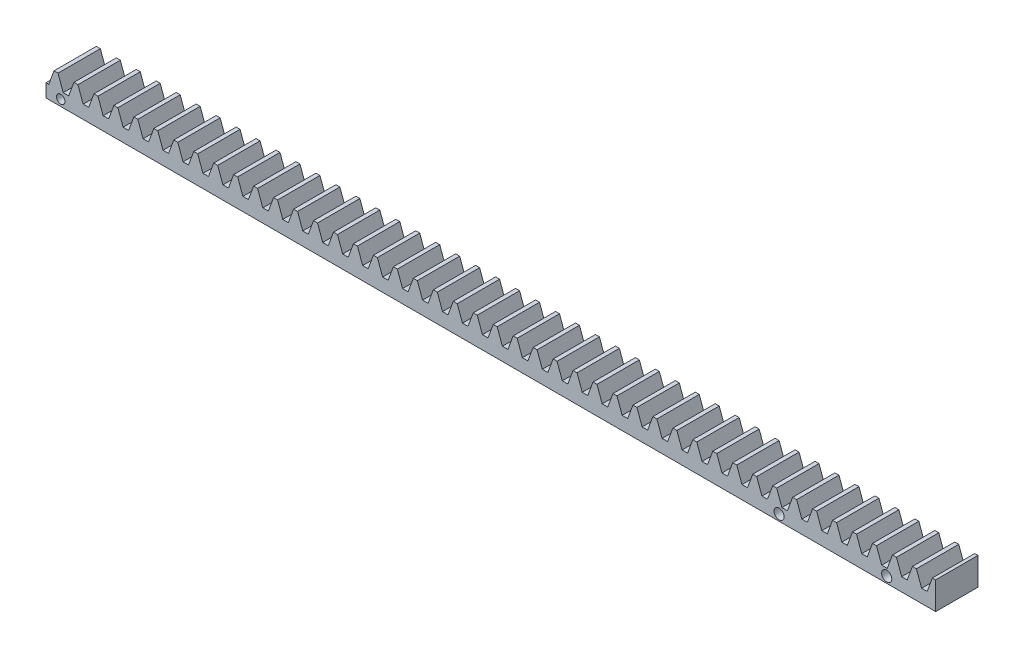
SolidWorks part; units mm, degrees
extrude "Blank" add sketch "BlankSke" against normal blind 10
sketch "BlankSke" plane through (0, 0, 0) normal (0, 0, 1) x (1, 0, 0)
  line L1 (0, 0) -> (210, 0)
  line L2 (0, 0) -> (0, 6.5)
  line L3 (0, 6.5) -> (210, 6.5)
  line L4 (210, 0) -> (210, 6.5)
  dimension "Length" = 210
  dimension "Blank_height" = 6.5
ref_plane "Plane1" through (0, 0, 0) normal (0, 0, 1) x (1, 0, 0)
ref_plane "Plane2" through (0, 0, 0) normal (0, 1, 0) x (1, 0, 0)
ref_plane "Plane3" through (0, 0, 0) normal (1, 0, 0) x (0, 0, -1)
sketch "HoldingSke" plane through (0, 0, 0) normal (0, 1, 0) x (1, 0, 0)
  line L0 (0, 0) -> (0.0928, 0.6602)
  line L1 (-15, 0) -> (100, 0) construction
  line L2 (0, 0) -> (-2.1039, 2.3779)
  line L3 (0, 0) -> (-11.863, 4.5341)
  line L4 (0, 0) -> (5.9991, 6.2122)
  line L5 (0, 0) -> (-23.7986, -8.8762)
  line L6 (0, 0) -> (-10.5278, -7.1032)
  line L9 (-71.009, 38.7566) -> (126.3265, 110.5808)
  line L10 (-76.2, 3.8779) -> (-71.2, 3.8779)
  line L11 (0, 0) -> (-10, 0)
  line L12 (-76.2, 101.6) -> (-76.147, 101.6)
  line L13 (24.9733, 27.94) -> (52.9518, 28.4284)
  line L14 (24.9733, 27.94) -> (24.9743, 27.94)
  line L15 (24.9733, 27.94) -> (100.4006, 29.5858)
  circle A0 centre (0, 0) radius 19.05
  circle A1 centre (0, 0) radius 2.5
  circle A2 centre (0, 0) radius 12.7
  dimension "MPH" = 5
  dimension "Diameter" = 38.1
  dimension "Num_teeth" = 46
  dimension "Pitch" = 0.6667
  dimension "Show_teeth" = 998
  dimension "Thickness" = 12.7
  dimension "Ap" = 20
  dimension "Pitch_height" = 5
  dimension "Width" = 10
  dimension "Backlash" = 0.053
  dimension "Addendum_fac" = 1
  dimension "Dedendum_fac" = 1.25
  dimension "Clearance_fac" = 0.25
  dimension "Dedendum_add" = 0.001
  dimension "Length" = 210
  dimension "Module" = 1.5
sketch "TooCutSkeIll" plane through (0, 0, 0) normal (0, 0, 1) x (1, 0, 0)
  line L0 (-1.8687, 6.4605) -> (-0.7447, 3.3724)
  line L1 (-0.3914, 3.125) -> (0.3914, 3.125)
  line L2 (0.7447, 3.3724) -> (1.8687, 6.4605)
  line L3 (210, 6.5) -> (0, 6.5) construction
  line L4 (0, 0) -> (0, 64.897) construction
  line L5 (-13.208, 5) -> (12.954, 5) construction
  line L6 (0, 0) -> (210, 0) construction
  line L7 (1.3371, 5) -> (1.3371, 48.7463) construction
  line L8 (-1.3371, 5) -> (-1.3371, 48.7463) construction
  line L9 (1.9251, 6.5) -> (1.9251, 6.5254)
  line L10 (-1.9251, 6.5) -> (-1.9251, 6.5254)
  line L11 (-1.9251, 6.5254) -> (1.9251, 6.5254)
  arc A0 (0.3914, 3.125) -> (0.7447, 3.3724) centre (0.3914, 3.501) ccw
  arc A1 (-0.7447, 3.3724) -> (-0.3914, 3.125) centre (-0.3914, 3.501) ccw
  arc A2 (1.9251, 6.5) -> (1.8687, 6.4605) centre (1.9251, 6.44) ccw
  arc A3 (-1.8687, 6.4605) -> (-1.9251, 6.5) centre (-1.9251, 6.44) ccw
  dimension "Pitch_height" = 5
  dimension "Addendum_plus" = 1.5254
  dimension "Pressure_angle" = 20
  dimension "Gap_width" = 2.6742
  dimension "Dedendum" = 1.875
extrude "ToothCutIll" [suppressed] cut sketch "TooCutSkeIll" against normal through all
sketch "TooCutSkeSim" plane through (0, 0, 0) normal (0, 0, 1) x (1, 0, 0)
  line L0 (0.6547, 3.125) -> (-0.6547, 3.125)
  line L1 (1.8923, 6.5254) -> (0.6547, 3.125)
  line L2 (0, 17.4625) -> (0, 53.467) construction
  line L3 (1.8923, 6.5254) -> (-1.8923, 6.5254)
  line L6 (-1.8923, 6.5254) -> (-0.6547, 3.125)
  line L9 (-1.3371, 5) -> (1.3371, 5) construction
  line L10 (0, 0) -> (210, 0) construction
  line L11 (1.3371, 5) -> (1.3371, 53.467) construction
  line L12 (-1.3371, 5) -> (-1.3371, 53.467) construction
  dimension "Pitch_height" = 5
  dimension "Addendum_plus" = 1.5254
  dimension "Pressure_angle" = 20
  dimension "Gap_width" = 2.6742
  dimension "Dedendum" = 1.875
extrude "ToothCutSim" cut sketch "TooCutSkeSim" against normal through all
pattern_linear "TeethCuts" count 45 spacing 4.7124 along (1, 0, 0) of "ToothCutIll", "ToothCutSim"
sketch "Sketch1" plane through (0, 0, -10) normal (0, 0, -1) x (-1, 0, 0)
  line L0 (0, 0) -> (-210, 0) construction
  line L1 (-199.6484, 1.5) -> (-3.4664, 1.5) construction
  circle A0 centre (-3.4664, 1.5) radius 1
  circle A2 centre (-198.4484, 1.5) radius 1.2
  circle A3 centre (-173.0484, 1.5) radius 1.2
  dimension "D2" = 1.5
  dimension "D3" = 25.4
extrude "Cut-Extrude1" cut sketch "Sketch1" against normal blind 10
equation "' \"Module@HoldingSke\" = 6.35"
equation "' \"Num_teeth@HoldingSke\" = 12"
equation "' \"Ap@HoldingSke\" =  20"
equation "' \"Ap@HoldingSke\" = 20"
equation "' \"Width@HoldingSke\" = 0.25 * 25.4"
equation "' \"Show_teeth@HoldingSke\" = 500"
equation "' \"Backlash@HoldingSke\" = 0.009 * 25.4"
equation "' \"Addendum_fac@HoldingSke\" = 1.0"
equation "' \"Dedendum_fac@HoldingSke\" = 1.25"
equation "' \"Dedendum_add@HoldingSke\" = 0.00005 * 25.4"
equation "' \"Clearance_fac@HoldingSke\" = 0.25"
equation "' \"Pitch_height@HoldingSke\" = 1 * 25.4"
equation "' \"Length@HoldingSke\" = 4.71 * 25.4"
equation "\"Pitch@HoldingSke\" = 1 / \"Module@HoldingSke\""
equation "\"MPH@HoldingSke\" = \"Dedendum_fac@HoldingSke\" / \"Pitch@HoldingSke\" + 2 * \"Dedendum_add@HoldingSke\" + 0.002 * 25.4"
equation "\"MPH@HoldingSke\" = ((sgn( \"MPH@HoldingSke\" - \"Pitch_height@HoldingSke\")+1)*( \"MPH@HoldingSke\" - \"Pitch_height@HoldingSke\"))/2 + \"Pitch_height@HoldingSke\""
equation "\"Blank_height@BlankSke\" = \"Pitch_height@HoldingSke\" + \"Addendum_fac@HoldingSke\"  / \"Pitch@HoldingSke\" "
equation "\"Length@BlankSke\" =  \"Length@HoldingSke\""
equation "\"Face_width@Blank\" = \"Width@HoldingSke\""
equation "\"Pressure_angle@TooCutSkeIll\" = \"Ap@HoldingSke\""
equation "\"Addendum_plus@TooCutSkeIll\" =  \"Addendum_fac@HoldingSke\"  / \"Pitch@HoldingSke\" + 0.001 *25.4"
equation "\"Dedendum@TooCutSkeIll\" = \"Dedendum_fac@HoldingSke\"  / \"Pitch@HoldingSke\""
equation "\"Pitch_height@TooCutSkeIll\" =  \"MPH@HoldingSke\""
equation "\"Gap_width@TooCutSkeIll\" = 3.14159265 / 2 / \"Pitch@HoldingSke\" + 6 * \"Backlash@HoldingSke\""
equation "\"Pressure_angle@TooCutSkeSim\" = \"Ap@HoldingSke\""
equation "\"Addendum_plus@TooCutSkeSim\" =  \"Addendum_fac@HoldingSke\"  / \"Pitch@HoldingSke\" + 0.001 * 25.4"
equation "\"Dedendum@TooCutSkeSim\" = \"Dedendum_fac@HoldingSke\"  / \"Pitch@HoldingSke\""
equation "\"Pitch_height@TooCutSkeSim\" =  \"MPH@HoldingSke\""
equation "\"Gap_width@TooCutSkeSim\" = 3.14159265 / 2 / \"Pitch@HoldingSke\" + 6 * \"Backlash@HoldingSke\""
equation "\"Root_fillet@TooCutSkeIll\" = \"Clearance_fac@HoldingSke\" / \"Pitch@HoldingSke\" + \"Dedendum_add@HoldingSke\""
equation "\"Break_rad@TooCutSkeIll\" = 0.02 / \"Pitch@HoldingSke\" * 2"
equation "\"Linear_pitch@TeethCuts\" = 3.14159265 / \"Pitch@HoldingSke\""
equation "\"Num_teeth@HoldingSke\" = int( ( \"Length@HoldingSke\" + 0 ) / (3.14159265 / \"Pitch@HoldingSke\")) + 0.9999  + 1"
equation " \"Num_teeth@TeethCuts\" = int( \"Show_teeth@HoldingSke\" ) + 1"
equation " \"Num_teeth@TeethCuts\" = ((sgn( \"Num_teeth@TeethCuts\" - \"Num_teeth@HoldingSke\" )-1)*( \"Num_teeth@TeethCuts\" - \"Num_teeth@HoldingSke\" ))/-2+ \"Num_teeth@HoldingSke\""
equation " \"Num_teeth@TeethCuts\" = ((sgn( \"Num_teeth@TeethCuts\" - 2.0)+1)*( \"Num_teeth@TeethCuts\" - 2.0))/2 +2.0"
